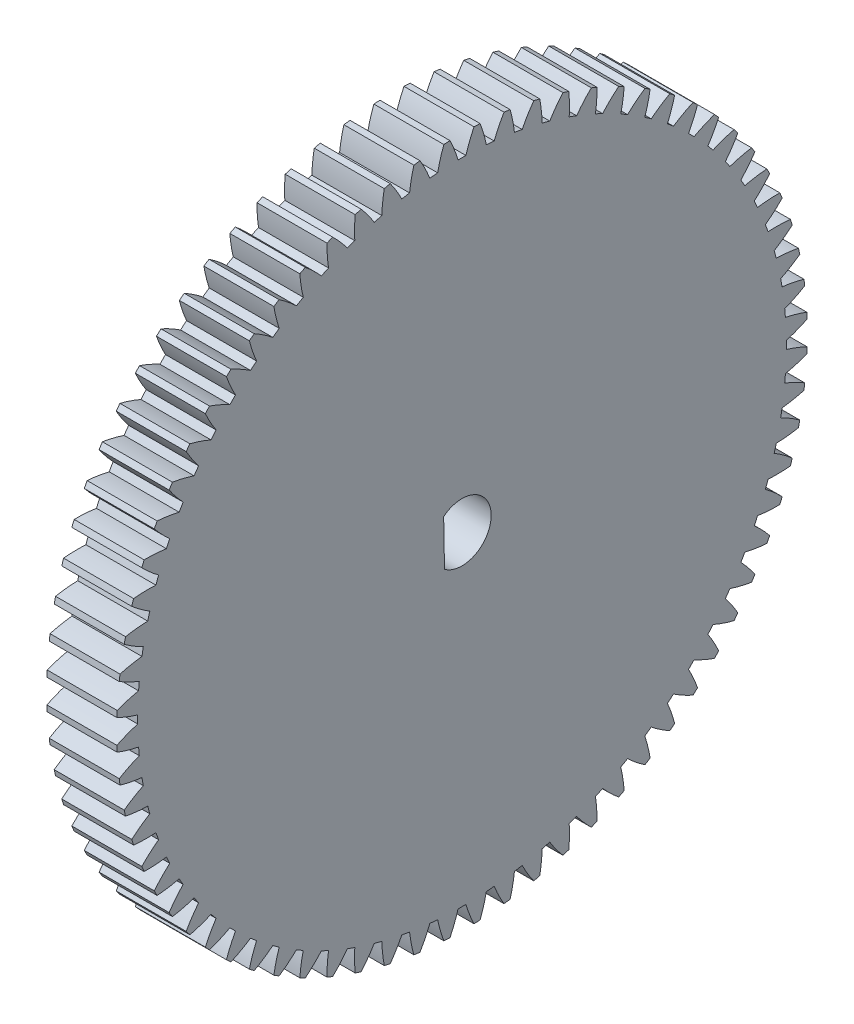
SolidWorks part; units mm, degrees
ref_plane "Plane1" through (0, 0, 0) normal (0, 0, 1) x (1, 0, 0)
ref_plane "Plane2" through (0, 0, 0) normal (0, 1, 0) x (1, 0, 0)
ref_plane "Plane3" through (0, 0, 0) normal (1, 0, 0) x (0, 0, -1)
sketch "HoldingSke" plane through (0, 0, 0) normal (0, 1, 0) x (1, 0, 0)
  line L0 (0, 0) -> (0.3863, -1.1888)
  line L1 (-15, 0) -> (100, 0) construction
  line L2 (0, 0) -> (-2.1039, 2.3779)
  line L3 (0, 0) -> (-11.863, 4.5341)
  line L4 (0, 0) -> (2.6687, 8.2133)
  line L5 (0, 0) -> (-46.8476, -17.4728)
  line L6 (0, 0) -> (-9.9476, -6.7116)
  line L7 (-2.1039, 2.3779) -> (8.6586, 51.206)
  line L8 (-76.2, 54.61) -> (-75.3, 54.61)
  line L9 (-71.009, 38.7566) -> (-53.1078, 45.2721)
  line L10 (-76.2, 71.12) -> (104.1128, 71.12)
  line L11 (0, 0) -> (-12, 0)
  line L12 (-76.2, 101.6) -> (-76.17, 101.6)
  line L13 (24.9733, 27.94) -> (52.9518, 28.4284)
  line L14 (24.9733, 27.94) -> (24.9743, 27.94)
  line L15 (24.9733, 27.94) -> (100.4006, 29.5858)
  line L16 (-63.627, -0.8) -> (-12.827, -0.8)
  circle A0 centre (0, 0) radius 2.5
  circle A1 centre (0, 0) radius 27.799
  circle A2 centre (0, 0) radius 37.5
  circle A3 centre (0, 0) radius 2.5
  dimension "MHD" = 55.598
  dimension "Hub_dia" = 75
  dimension "Bore" = 5
  dimension "MBD" = 5
  dimension "Num_teeth" = 72
  dimension "Pitch" = 1.25
  dimension "Overall_len" = 50
  dimension "Show_teeth" = 72
  dimension "Thickness" = 12
  dimension "OAL" = 50.0002
  dimension "T_dim" = 0.9
  dimension "Ap" = 20
  dimension "H" = 19.05
  dimension "Pitch_radius" = 180.3128
  dimension "Width" = 12
  dimension "Backlash" = 0.03
  dimension "Addendum_fac" = 1
  dimension "Dedendum_fac" = 1.25
  dimension "Clearance_fac" = 0.25
  dimension "Dedendum_add" = 0.001
  dimension "Module" = 0.8
sketch "BasProSke" plane through (0, 0, 0) normal (0, 1, 0) x (1, 0, 0)
  line L0 (-10, 0) -> (60, 0) construction
  line L1 (0, 0) -> (0, 29.6)
  line L2 (0, 0) -> (6, 0)
  line L3 (6, 0) -> (6, 29.6)
  line L4 (6, 29.6) -> (0, 29.6)
  dimension "Thickness" = 6
  dimension "Diameter" = 59.2
revolve "Base-Revolve" add sketch "BasProSke" angle 360 about L0
sketch "TooCutSke" plane through (0, 0, 0) normal (1, 0, 0) x (0, 0, -1)
  line L1 (0, 0) -> (0, 107) construction
  line L2 (0, 0) -> (-0.6808, 28.792) construction
  line L3 (0, 0) -> (-2.512, 57.5337) construction
  line L4 (-0.6808, 28.792) -> (-1.256, 28.7668) construction
  arc A0 (0.3383, 27.7969) -> (-0.3383, 27.7969) centre (0, 0) ccw
  arc A1 (1.0408, 29.6071) -> (-1.0408, 29.6071) centre (0, 0) ccw
  circle A2 centre (0, 0) radius 28.8 construction
  circle A3 centre (0, 0) radius 27.0631 construction
  arc A4 (-0.3383, 27.7969) -> (-1.0408, 29.6071) centre (-11.391, 24.5491) ccw
  arc A5 (1.0408, 29.6071) -> (0.3383, 27.7969) centre (11.391, 24.5491) ccw
  dimension "Root_dia" = 55.598
  dimension "Overcut_dia" = 59.2508
  dimension "Pitch_dia" = 57.6
  dimension "Base_dia" = 54.1263
  dimension "Flank_rad" = 11.52
  dimension "Half_ang" = 2.5
  dimension "Half_CT" = 0.5758
extrude "ToothCut" cut sketch "TooCutSke" along normal through all
fillet "Breaks" [suppressed] radius 0.016
fillet "RootFillets" [suppressed] radius 0.201
pattern_circular "TeethCuts" count 72 every 5 about axis through (-10, 0, 0) along (1, 0, 0) of "ToothCut", "RootFillets", "Breaks"
sketch "HubNeaOneSke" plane through (0, 0, 0) normal (-1, 0, 0) x (0, 0, 1)
  circle A0 centre (0, 0) radius 27.799
  dimension "Diameter" = 55.598
extrude "HubNearOne" [suppressed] add sketch "HubNeaOneSke" along normal blind 44.0002
sketch "HubNeaBotSke" plane through (0, 0, 0) normal (-1, 0, 0) x (0, 0, 1)
  circle A0 centre (0, 0) radius 27.799
  dimension "Diameter" = 55.598
extrude "HubNearBoth" [suppressed] add sketch "HubNeaBotSke" along normal blind 22.0001
ref_plane "FarPln" through (6, 0, 0) normal (1, 0, 0) x (0, 0, -1)
sketch "HubFarSke" plane through (6, 0, 0) normal (1, 0, 0) x (0, 0, -1)
  circle A0 centre (0, 0) radius 27.799
  dimension "Diameter" = 55.598
extrude "HubFar" [suppressed] add sketch "HubFarSke" along normal blind 22.0001
sketch "BorSke" plane through (0, 0, 0) normal (1, 0, 0) x (0, 0, -1)
  circle A0 centre (0, 0) radius 2.5
  dimension "Diameter" = 5
extrude "Bore" cut sketch "BorSke" along normal mid plane 100.0004
sketch "KeySke" plane through (0, 0, 0) normal (1, 0, 0) x (0, 0, -1)
  line L0 (-1, 0) -> (-1, 3.4)
  line L1 (-1, 3.4) -> (1, 3.4)
  line L2 (1, 3.4) -> (1, 0)
  line L3 (0, 0) -> (0, 34) construction
  line L4 (-1, 0) -> (1, 0)
  dimension "Offset" = 3.4
  dimension "Width" = 2
extrude "Keyway" [suppressed] cut sketch "KeySke" along normal mid plane 100.0004
pattern_circular "Keyway2" [suppressed] count 2 every 90 about axis through (-10, 0, 0) along (1, 0, 0)
sketch "Sketch1" plane through (6, 0, 0) normal (1, 0, 0) x (0, 0, -1)
  line L0 (-2.5, 0) -> (-1.5, 0) construction
  line L1 (-1.5724, 1.9436) -> (-1.5, -2)
  circle A0 centre (0, 0) radius 2.5 construction
  arc A1 (-1.5724, 1.9436) -> (-1.5, -2) centre (0, 0) ccw
extrude "Boss-Extrude1" add sketch "Sketch1" against normal blind 6 contours L0 A1 L1 | A1 L0 L1
equation "' \"Module@HoldingSke\" = 6.35"
equation "' \"Num_teeth@HoldingSke\" = 12"
equation "' \"Ap@HoldingSke\" =  20"
equation "' \"Ap@HoldingSke\" = 20"
equation "' \"Width@HoldingSke\" = 0.5 * 25.4"
equation "' \"Hub_dia@HoldingSke\"= 1 * 25.4"
equation "' \"Hub_dia@HoldingSke\" = 1 * 25.4"
equation "' \"Overall_len@HoldingSke\" = 1.0 * 25.4"
equation "' \"Bore@HoldingSke\" = 0.75 * 25.4"
equation "' \"T_dim@HoldingSke\" = 0.1 * 25.4"
equation "' \"Width@KeySke\" = 0.25 * 25.4"
equation "' \"Show_teeth@HoldingSke\" = 13"
equation "' \"Backlash@HoldingSke\" = 0.009 * 25.4"
equation "' \"Addendum_fac@HoldingSke\" = 1.0"
equation "' \"Dedendum_fac@HoldingSke\" = 1.25"
equation "' \"Dedendum_add@HoldingSke\" = 0.00005 * 25.4"
equation "' \"Clearance_fac@HoldingSke\" = 0.25"
equation "\"Pitch@HoldingSke\" = 1 / \"Module@HoldingSke\""
equation "\"Overcut_dia@TooCutSke\" = (\"Num_teeth@HoldingSke\" + 2 * \"Addendum_fac@HoldingSke\") / \"Pitch@HoldingSke\" + 0.002 * 25.4"
equation "\"Pitch_dia@TooCutSke\" = \"Num_teeth@HoldingSke\" / \"Pitch@HoldingSke\""
equation "\"Base_dia@TooCutSke\" = \"Num_teeth@HoldingSke\" / \"Pitch@HoldingSke\" * cos((\"Ap@HoldingSke\"  * 3.14159265 / 180))"
equation "\"Root_dia@TooCutSke\" = (\"Num_teeth@HoldingSke\" + 2) / \"Pitch@HoldingSke\" - 2 * (\"Addendum_fac@HoldingSke\" + \"Dedendum_fac@HoldingSke\") / \"Pitch@HoldingSke\" - \"Dedendum_add@HoldingSke\" * 2"
equation "\"Half_ang@TooCutSke\" = 180 / \"Num_teeth@HoldingSke\""
equation "\"Half_CT@TooCutSke\" = \"Num_teeth@HoldingSke\" / \"Pitch@HoldingSke\" * sin((3.14159265 / 2 / \"Num_teeth@HoldingSke\")) / 2 - 7 * \"Backlash@HoldingSke\" / 4"
equation "\"Flank_rad@TooCutSke\" = \"Num_teeth@HoldingSke\" / \"Pitch@HoldingSke\" / 5"
equation "\"Radius@RootFillets\" = \"Clearance_fac@HoldingSke\" / \"Pitch@HoldingSke\" + \"Dedendum_add@HoldingSke\""
equation "\"Break_rad@Breaks\" = 0.02 / \"Pitch@HoldingSke\""
equation "\"Thickness@HoldingSke\" = \"Width@HoldingSke\""
equation "\"OAL@HoldingSke\" = \"Thickness@HoldingSke\""
equation "\"MHD@HoldingSke\" = (\"Num_teeth@HoldingSke\" + 2) / \"Pitch@HoldingSke\" - 2 * (\"Addendum_fac@HoldingSke\" + \"Dedendum_fac@HoldingSke\")  / \"Pitch@HoldingSke\" - \"Dedendum_add@HoldingSke\" * 2"
equation "\"MBD@HoldingSke\" = (\"Num_teeth@HoldingSke\" + 2) / \"Pitch@HoldingSke\" - 2 * (\"Addendum_fac@HoldingSke\" + \"Dedendum_fac@HoldingSke\")  / \"Pitch@HoldingSke\" - \"Dedendum_add@HoldingSke\" * 2 - 0.002 * 25.4"
equation "\"MHD@HoldingSke\" = ((sgn( \"MHD@HoldingSke\" - \"Hub_dia@HoldingSke\" )-1)*( \"MHD@HoldingSke\" - \"Hub_dia@HoldingSke\" ))/-2+ \"Hub_dia@HoldingSke\""
equation "\"MBD@HoldingSke\" = ((sgn( \"MBD@HoldingSke\" - \"Bore@HoldingSke\" )-1)*( \"MBD@HoldingSke\" - \"Bore@HoldingSke\" ))/-2+ \"Bore@HoldingSke\""
equation "\"OAL@HoldingSke\" = ((sgn( \"OAL@HoldingSke\" - \"Overall_len@HoldingSke\" )+1)*( \"OAL@HoldingSke\" - \"Overall_len@HoldingSke\" ))/2 + \"Overall_len@HoldingSke\" + 0.000002 * 25.4"
equation "\"Num_teeth@TeethCuts\" = int( \"Show_teeth@HoldingSke\" ) + 1"
equation "\"Num_teeth@TeethCuts\" = ((sgn( \"Num_teeth@TeethCuts\" - \"Num_teeth@HoldingSke\" )-1)*( \"Num_teeth@TeethCuts\" - \"Num_teeth@HoldingSke\" ))/-2+ \"Num_teeth@HoldingSke\""
equation "\"Num_teeth@TeethCuts\" = ((sgn( \"Num_teeth@TeethCuts\" - 2.0)+1)*( \"Num_teeth@TeethCuts\" - 2.0))/2 +2.0"
equation "\"Angle@TeethCuts\" = 360.0 / \"Num_teeth@HoldingSke\""
equation "\"Diameter@BasProSke\" = (\"Num_teeth@HoldingSke\" + 2 * \"Addendum_fac@HoldingSke\") / \"Pitch@HoldingSke\""
equation "\"Thickness@BasProSke\" = 6"
equation "' \"Fillet_rad@BasProSke\" =  \"Thickness@HoldingSke\" * 0.05"
equation "' \"Fillet_rad@BasProSke\" = \"Thickness@HoldingSke\" * 0.05"
equation "\"MHD@HoldingSke\" = ((sgn( \"MHD@HoldingSke\" - \"Root_dia@TooCutSke\" )-1)*( \"MHD@HoldingSke\" - \"Root_dia@TooCutSke\" ))/-2+ \"Root_dia@TooCutSke\""
equation "\"Diameter@HubNeaOneSke\" = \"MHD@HoldingSke\""
equation "\"Length@HubNearOne\" = \"OAL@HoldingSke\" - \"Thickness@BasProSke\""
equation "\"Diameter@HubNeaBotSke\" = \"MHD@HoldingSke\""
equation "\"Length@HubNearBoth\" = ( \"OAL@HoldingSke\" - \"Thickness@BasProSke\" ) / 2.0"
equation "\"Thickness@FarPln\" = \"Thickness@BasProSke\""
equation "\"Diameter@HubFarSke\" = \"MHD@HoldingSke\""
equation "\"Length@HubFar\" = ( \"OAL@HoldingSke\" - \"Thickness@BasProSke\" ) / 2.0"
equation "\"Diameter@BorSke\" = \"MBD@HoldingSke\""
equation "\"D1@Bore\" = \"OAL@HoldingSke\" * 2.0"
equation "\"D1@Keyway\" = \"OAL@HoldingSke\" * 2.0"
equation "\"Offset@KeySke\" = \"T_dim@HoldingSke\" + \"MBD@HoldingSke\" / 2.0"
